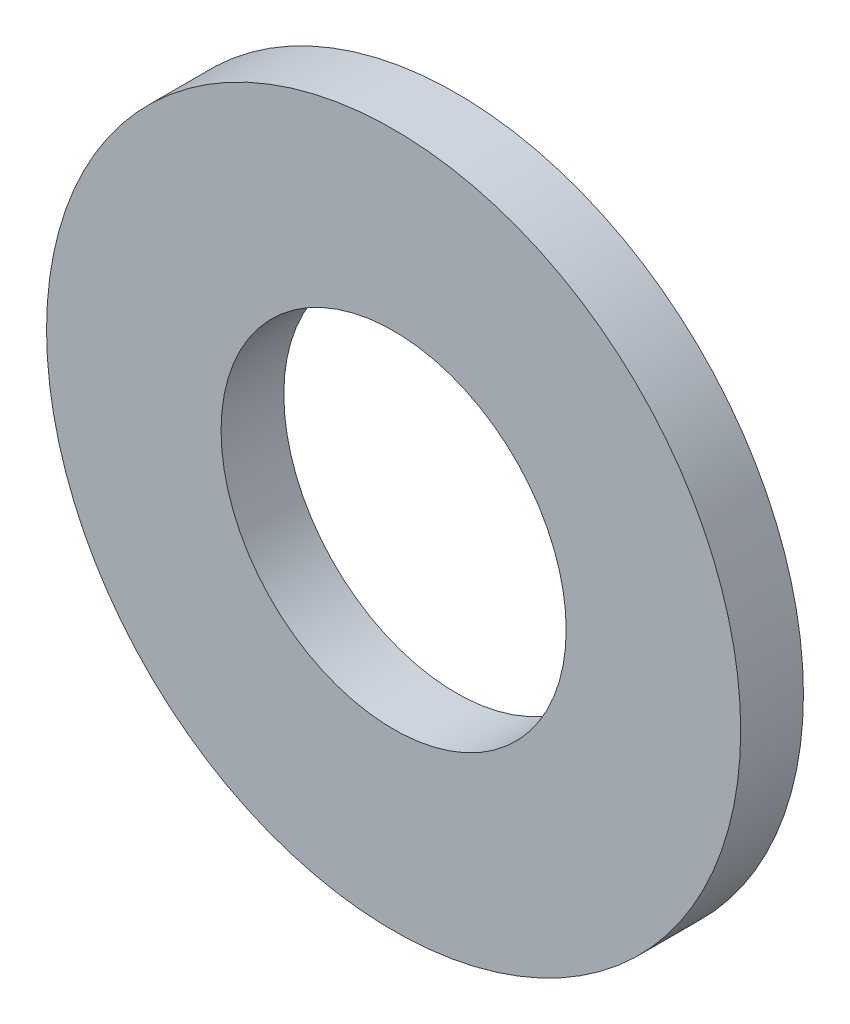
SolidWorks part; units mm, degrees
material "STAINLESS STEEL, 316S16"
ref_plane "Front Plane" through (0, 0, 0) normal (0, 0, 1) x (1, 0, 0)
ref_plane "Top Plane" through (0, 0, 0) normal (0, 1, 0) x (1, 0, 0)
ref_plane "Right Plane" through (0, 0, 0) normal (1, 0, 0) x (0, 0, -1)
sketch "Sketch1" plane through (0, 0, 0) normal (0, 0, 1) x (1, 0, 0)
  circle A0 centre (0, 0) radius 2.2
  circle A1 centre (0, 0) radius 4.425
  dimension "A" = 4.4
  dimension "B" = 8.85
extrude "Boss-Extrude1" add sketch "Sketch1" along normal blind 0.8
